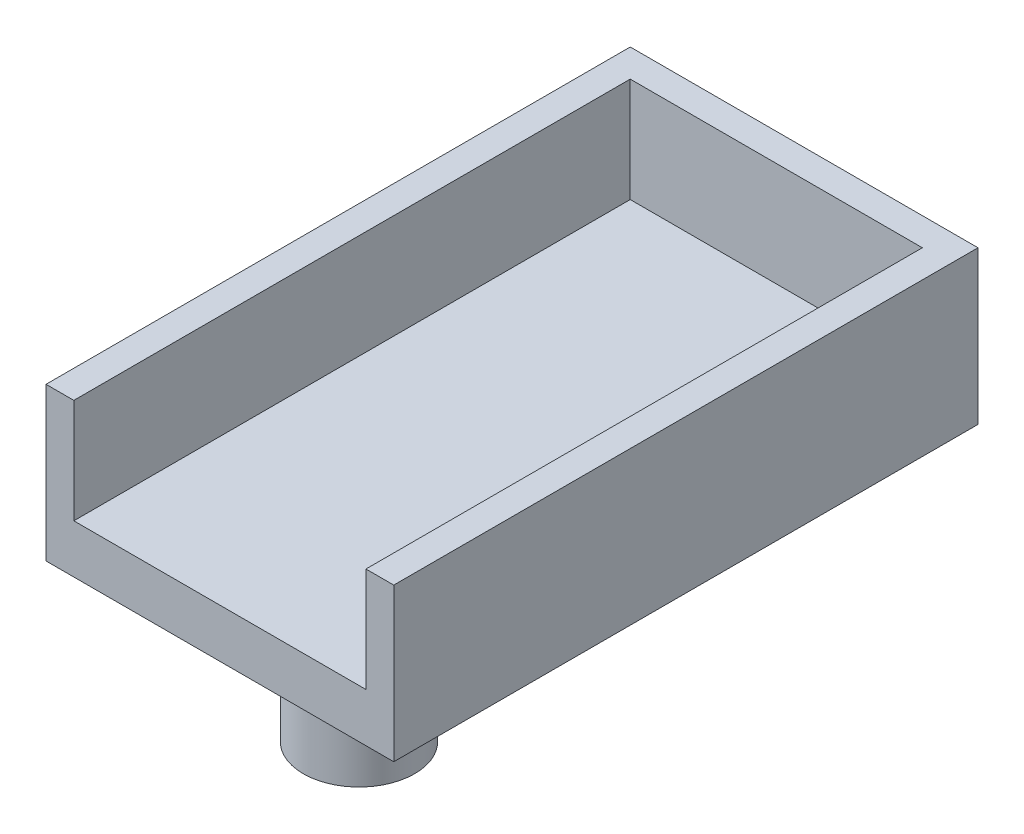
SolidWorks part; units mm, degrees
ref_plane "Front Plane" through (0, 0, 0) normal (0, 0, 1) x (1, 0, 0)
ref_plane "Top Plane" through (0, 0, 0) normal (0, 1, 0) x (1, 0, 0)
ref_plane "Right Plane" through (0, 0, 0) normal (1, 0, 0) x (0, 0, -1)
sketch "Sketch1" plane through (0, 0, 0) normal (0, 1, 0) x (1, 0, 0)
  line L1 (0, 40) -> (25, 40)
  line L2 (0, 40) -> (0, 0)
  line L3 (0, 0) -> (25, 0)
  line L4 (25, 40) -> (25, 0)
  dimension "D1" = 25
  dimension "D2" = 40
extrude "Boss-Extrude1" add sketch "Sketch1" along normal blind 3.5
sketch "Sketch2" plane through (0, 3.5, 0) normal (0, 1, 0) x (1, 0, 0)
  line L0 (25, 40) -> (0, 40) construction
  line L1 (0, 0) -> (2, 0)
  line L2 (0, 0) -> (0, 40)
  line L3 (0, 40) -> (2, 40)
  line L4 (2, 0) -> (2, 40)
  line L5 (0, 0) -> (25, 0) construction
  line L6 (25, 40) -> (23, 40)
  line L7 (25, 40) -> (25, 0)
  line L8 (25, 0) -> (23, 0)
  line L9 (23, 40) -> (23, 0)
  dimension "D1" = 2
  dimension "D2" = 2
extrude "Boss-Extrude2" add sketch "Sketch2" along normal blind 7.5
sketch "Sketch3" plane through (0, 0, 0) normal (0, -1, 0) x (-1, 0, 0)
  line L0 (0, 0) -> (-25, 0) construction
  circle A0 centre (-12.5, 10) radius 4
  point P2 (-12.5, 0)
  dimension "D1" = 8
  dimension "D2" = 10
extrude "Boss-Extrude3" add sketch "Sketch3" along normal blind 10
sketch "Sketch4" plane through (0, 0, -40) normal (0, 0, -1) x (-1, 0, 0)
  line L1 (-25, 11) -> (0, 11)
  line L2 (-25, 11) -> (-25, 0)
  line L3 (-25, 0) -> (0, 0)
  line L4 (0, 11) -> (0, 0)
extrude "Boss-Extrude4" add sketch "Sketch4" along normal blind 2 contours L1 L4 L3 L2
